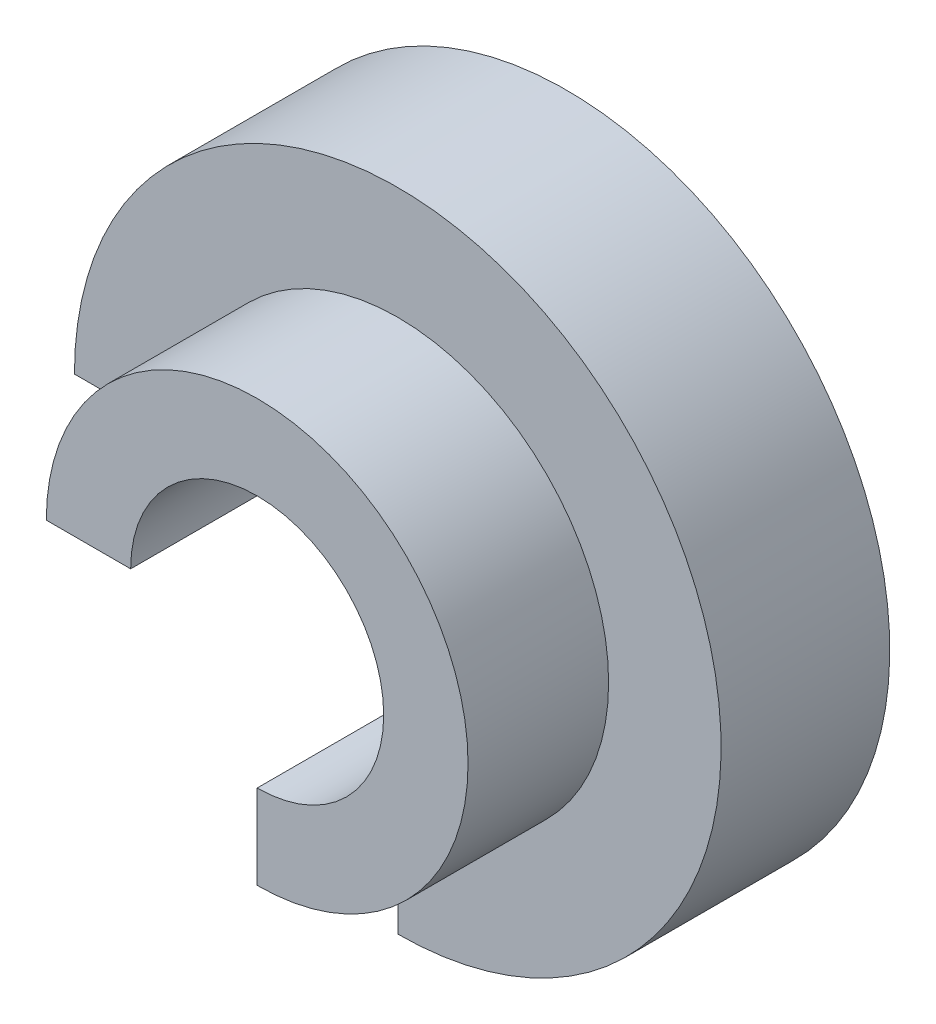
SolidWorks part; units mm, degrees
ref_plane "Front Plane" through (0, 0, 0) normal (0, 0, 1) x (1, 0, 0)
ref_plane "Top Plane" through (0, 0, 0) normal (0, 1, 0) x (1, 0, 0)
ref_plane "Right Plane" through (0, 0, 0) normal (1, 0, 0) x (0, 0, -1)
sketch "Sketch1" plane through (0, 0, 0) normal (0, 1, 0) x (1, 0, 0)
  line L0 (0, -150) -> (0, 150) construction
  line L1 (-60, 150) -> (-110, 150)
  line L2 (-110, 150) -> (-110, 110)
  line L3 (-110, 110) -> (-170, 110)
  line L4 (-170, 110) -> (-170, 70)
  line L5 (-170, 70) -> (-230, 70)
  line L6 (-230, 70) -> (-230, -50)
  line L7 (-230, -50) -> (-150, -50)
  line L8 (-150, -50) -> (-150, -150)
  line L9 (-150, -150) -> (-90, -150)
  line L10 (-90, -150) -> (-90, -30)
  line L11 (-90, -30) -> (-180, -30)
  line L12 (-180, -30) -> (-180, 40)
  line L13 (-180, 40) -> (-130, 40)
  line L14 (-130, 40) -> (-130, 80)
  line L15 (-130, 80) -> (-90, 80)
  line L16 (-90, 80) -> (-90, 110)
  line L19 (-90, 110) -> (-60, 110)
  line L20 (-60, 110) -> (-60, 150)
  point P2 (0, 0)
  dimension "D1" = 300
  dimension "D2" = 60
  dimension "D3" = 30
  dimension "D4" = 40
  dimension "D5" = 50
  dimension "D6" = 40
  dimension "D7" = 40
  dimension "D8" = 120
  dimension "D9" = 60
  dimension "D10" = 60
  dimension "D11" = 50
  dimension "D12" = 30
  dimension "D13" = 40
  dimension "D14" = 70
  dimension "D15" = 90
  dimension "D16" = 80
  dimension "D17" = 120
  dimension "D18" = 300
revolve "Revolve1" add sketch "Sketch1" angle 270 about L0
